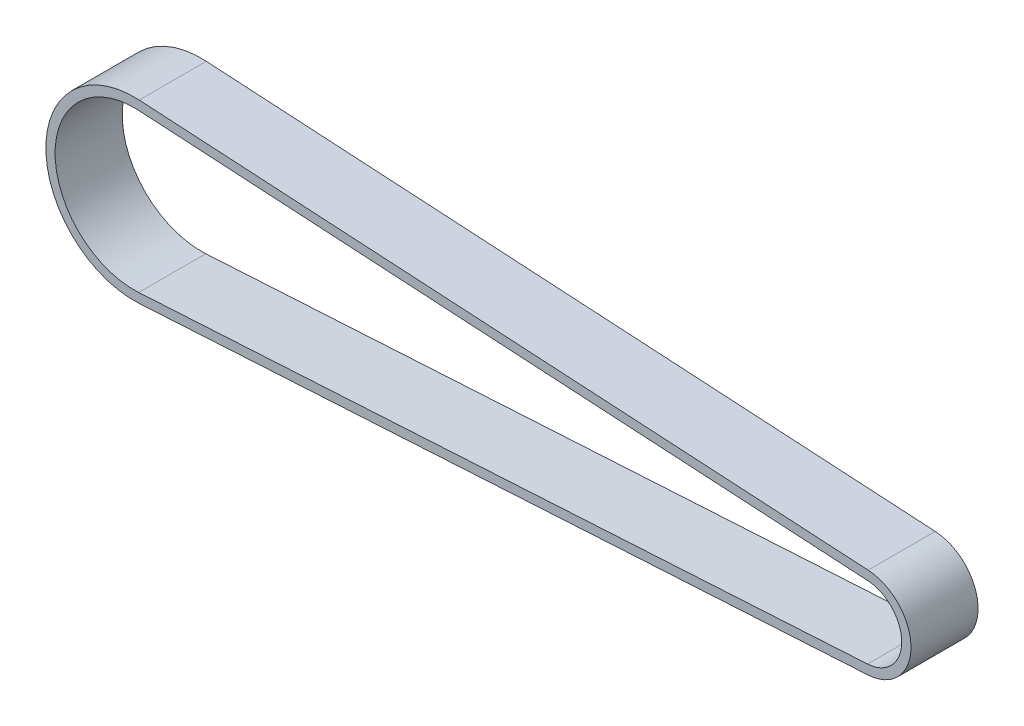
SolidWorks part; units mm, degrees
ref_plane "Front" through (0, 0, 0) normal (0, 0, 1) x (1, 0, 0)
ref_plane "Top" through (0, 0, 0) normal (0, 1, 0) x (1, 0, 0)
ref_plane "Right" through (0, 0, 0) normal (1, 0, 0) x (0, 0, -1)
sketch "Эскиз1" plane through (0, 0, 0) normal (0, 0, 1) x (1, 0, 0)
  line L0 (0, 0) -> (109, 0) construction
  line L1 (0.768, 13.1268) -> (109.3962, 6.7714)
  line L2 (109.3962, -6.7714) -> (0.768, -13.1268)
  line L3 (109.3156, -5.3938) -> (0.6874, -11.7491)
  line L4 (0.6874, 11.7491) -> (109.3156, 5.3938)
  arc A0 (0.768, 13.1268) -> (0.768, -13.1268) centre (0, 0) ccw
  arc A1 (109.3962, -6.7714) -> (109.3962, 6.7714) centre (109, 0) ccw
  arc A2 (0.6874, 11.7491) -> (0.6874, -11.7491) centre (0, 0) ccw
  arc A3 (109.3156, -5.3938) -> (109.3156, 5.3938) centre (109, 0) ccw
  dimension "D1" = 26.2984
  dimension "D3" = 13.566
  dimension "D2" = 109
  dimension "D4" = 1.38
extrude "Бобышка-Вытянуть1" add sketch "Эскиз1" against normal blind 10
